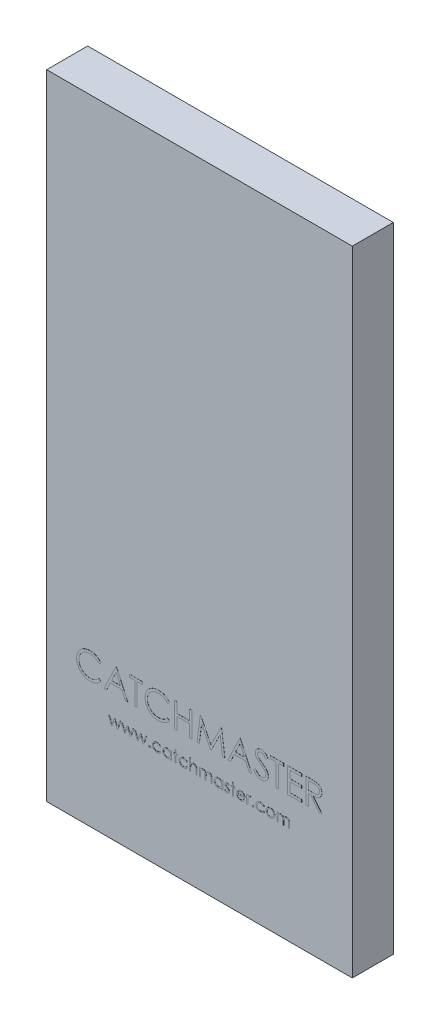
SolidWorks part; units mm, degrees
material "Balsa"
ref_plane "Front Plane" through (0, 0, 0) normal (0, 0, 1) x (1, 0, 0)
ref_plane "Top Plane" through (0, 0, 0) normal (0, 1, 0) x (1, 0, 0)
ref_plane "Right Plane" through (0, 0, 0) normal (1, 0, 0) x (0, 0, -1)
sketch "Sketch1" plane through (0, 0, 0) normal (0, 0, 1) x (1, 0, 0)
  line L1 (-42.1005, -87.3125) -> (42.1005, -87.3125)
  line L2 (-42.1005, -87.3125) -> (-42.1005, 87.3125)
  line L3 (-42.1005, 87.3125) -> (42.1005, 87.3125)
  line L4 (42.1005, -87.3125) -> (42.1005, 87.3125)
  line L5 (-42.1005, -87.3125) -> (42.1005, 87.3125) construction
  line L6 (-42.1005, 87.3125) -> (42.1005, -87.3125) construction
  point P0 (0, 0)
  dimension "D1" = 84.201
  dimension "D2" = 174.625
extrude "Boss-Extrude1" add sketch "Sketch1" along normal mid plane 11.303
sketch "Sketch2" plane through (0, 0, 5.6515) normal (0, 0, 1) x (1, 0, 0)
  line L0 (-42.1005, -60.325) -> (42.1005, -60.325) construction
  line L1 (-42.1005, 87.3125) -> (-42.1005, -87.3125) construction
  line L2 (42.1005, -87.3125) -> (42.1005, 87.3125) construction
  line L3 (-42.1005, -87.3125) -> (42.1005, -87.3125) construction
  line L4 (-42.1005, -52.3875) -> (42.1005, -52.3875) construction
  text T0 "www.catchmaster.com" font "Century Gothic" height 3.175
  text T1 "CATCHMASTER" font "Century Gothic" height in points 26
  dimension "D1" = 26.9875
  dimension "D2" = 34.925
extrude "Boss-Extrude2" add sketch "Sketch2" along normal blind 0.0254
